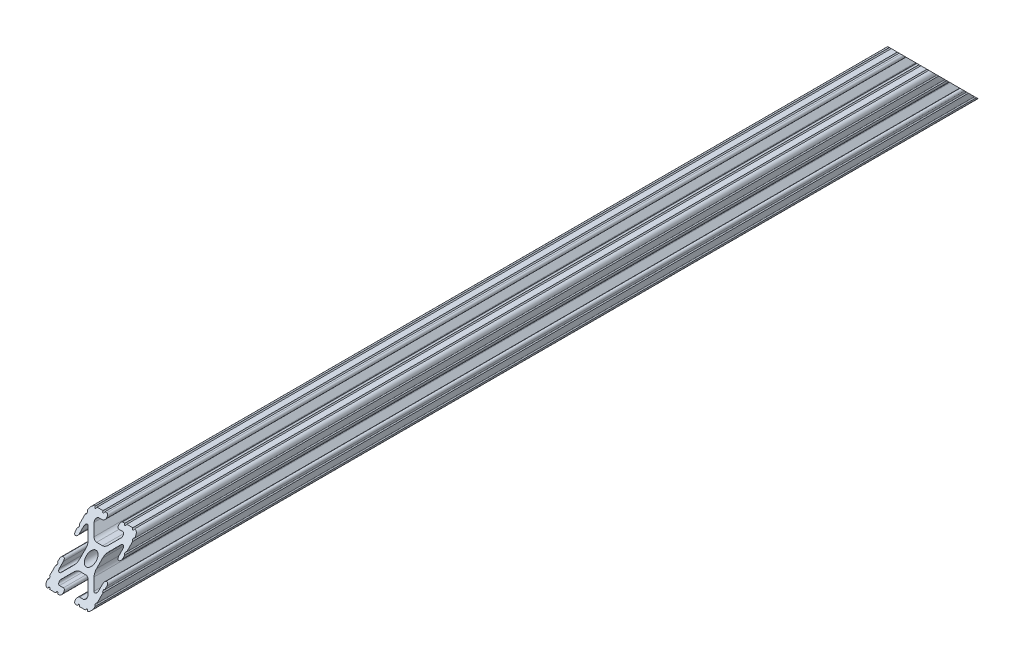
SolidWorks part; units mm, degrees
ref_plane "Front Plane" through (0, 0, 0) normal (0, 0, 1) x (1, 0, 0)
ref_plane "Top Plane" through (0, 0, 0) normal (0, 1, 0) x (1, 0, 0)
ref_plane "Right Plane" through (0, 0, 0) normal (1, 0, 0) x (0, 0, -1)
sketch "Sketch1" plane through (0, 0, 0) normal (0, 0, 1) x (1, 0, 0)
  line L0 (-12.7, -6.3331) -> (-12.7, -9.5504)
  line L1 (-9.5504, -12.7) -> (-6.3331, -12.7)
  line L2 (-5.3171, -12.7) -> (-4.3434, -12.7)
  line L3 (-4.3434, -10.4902) -> (-6.4748, -10.4902)
  line L4 (-7.1932, -8.7558) -> (-3.8632, -5.4257)
  line L5 (-1.6181, -4.4958) -> (1.6181, -4.4958)
  line L6 (3.8632, -5.4257) -> (7.1932, -8.7558)
  line L7 (6.4748, -10.4902) -> (4.3434, -10.4902)
  line L8 (4.3434, -12.7) -> (5.3171, -12.7)
  line L9 (6.3331, -12.7) -> (9.5504, -12.7)
  line L10 (12.7, -9.5504) -> (12.7, -6.3331)
  line L11 (12.7, -5.3171) -> (12.7, -4.3434)
  line L12 (10.4902, -4.3434) -> (10.4902, -6.4748)
  line L13 (8.7558, -7.1932) -> (5.4257, -3.8632)
  line L14 (4.4958, -1.6181) -> (4.4958, 1.6181)
  line L15 (5.4257, 3.8632) -> (8.7558, 7.1932)
  line L16 (10.4902, 6.4748) -> (10.4902, 4.3434)
  line L17 (12.7, 4.3434) -> (12.7, 5.3171)
  line L18 (12.7, 6.3331) -> (12.7, 9.5504)
  line L19 (9.5504, 12.7) -> (6.3331, 12.7)
  line L20 (5.3171, 12.7) -> (4.3434, 12.7)
  line L21 (4.3434, 10.4902) -> (6.4748, 10.4902)
  line L22 (7.1932, 8.7558) -> (3.8632, 5.4257)
  line L23 (1.6181, 4.4958) -> (-1.6181, 4.4958)
  line L24 (-3.8632, 5.4257) -> (-7.1932, 8.7558)
  line L25 (-6.4748, 10.4902) -> (-4.3434, 10.4902)
  line L26 (-4.3434, 12.7) -> (-5.3171, 12.7)
  line L27 (-6.3331, 12.7) -> (-9.5504, 12.7)
  line L28 (-12.7, 9.5504) -> (-12.7, 6.3331)
  line L29 (-12.7, 5.3171) -> (-12.7, 4.3434)
  line L30 (-10.4902, 4.3434) -> (-10.4902, 6.4748)
  line L31 (-8.7558, 7.1932) -> (-5.4257, 3.8632)
  line L32 (-4.4958, 1.6181) -> (-4.4958, -1.6181)
  line L33 (-5.4257, -3.8632) -> (-8.7558, -7.1932)
  line L34 (-10.4902, -6.4748) -> (-10.4902, -4.3434)
  line L35 (-12.7, -4.3434) -> (-12.7, -5.3171)
  circle A0 centre (0, 0) radius 2.6035
  arc A1 (-12.7, -5.3171) -> (-12.7, -6.3331) centre (-12.7, -5.8251) cw
  arc A2 (-12.7, -9.5504) -> (-12.6998, -10.5664) centre (-12.7, -10.0584) cw
  arc A3 (-12.6998, -10.5664) -> (-10.5664, -12.6998) centre (-10.5918, -10.5918) ccw
  arc A4 (-10.5664, -12.6998) -> (-9.5504, -12.7) centre (-10.0584, -12.7) cw
  arc A5 (-6.3331, -12.7) -> (-5.3171, -12.7) centre (-5.8251, -12.7) cw
  arc A6 (-4.3434, -12.7) -> (-4.3434, -10.4902) centre (-4.3434, -11.5951) ccw
  arc A7 (-6.4748, -10.4902) -> (-7.1932, -8.7558) centre (-6.4748, -9.4742) cw
  arc A8 (-3.8632, -5.4257) -> (-1.6181, -4.4958) centre (-1.6181, -7.6708) cw
  arc A9 (1.6181, -4.4958) -> (3.8632, -5.4257) centre (1.6181, -7.6708) cw
  arc A10 (7.1932, -8.7558) -> (6.4748, -10.4902) centre (6.4748, -9.4742) cw
  arc A11 (4.3434, -10.4902) -> (4.3434, -12.7) centre (4.3434, -11.5951) ccw
  arc A12 (5.3171, -12.7) -> (6.3331, -12.7) centre (5.8251, -12.7) cw
  arc A13 (9.5504, -12.7) -> (10.5664, -12.6998) centre (10.0584, -12.7) cw
  arc A14 (10.5664, -12.6998) -> (12.6998, -10.5664) centre (10.5918, -10.5918) ccw
  arc A15 (12.6998, -10.5664) -> (12.7, -9.5504) centre (12.7, -10.0584) cw
  arc A16 (12.7, -6.3331) -> (12.7, -5.3171) centre (12.7, -5.8251) cw
  arc A17 (12.7, -4.3434) -> (10.4902, -4.3434) centre (11.5951, -4.3434) ccw
  arc A18 (10.4902, -6.4748) -> (8.7558, -7.1932) centre (9.4742, -6.4748) cw
  arc A19 (5.4257, -3.8632) -> (4.4958, -1.6181) centre (7.6708, -1.6181) cw
  arc A20 (4.4958, 1.6181) -> (5.4257, 3.8632) centre (7.6708, 1.6181) cw
  arc A21 (8.7558, 7.1932) -> (10.4902, 6.4748) centre (9.4742, 6.4748) cw
  arc A22 (10.4902, 4.3434) -> (12.7, 4.3434) centre (11.5951, 4.3434) ccw
  arc A23 (12.7, 5.3171) -> (12.7, 6.3331) centre (12.7, 5.8251) cw
  arc A24 (12.7, 9.5504) -> (12.6998, 10.5664) centre (12.7, 10.0584) cw
  arc A25 (12.6998, 10.5664) -> (10.5664, 12.6998) centre (10.5918, 10.5918) ccw
  arc A26 (10.5664, 12.6998) -> (9.5504, 12.7) centre (10.0584, 12.7) cw
  arc A27 (6.3331, 12.7) -> (5.3171, 12.7) centre (5.8251, 12.7) cw
  arc A28 (4.3434, 12.7) -> (4.3434, 10.4902) centre (4.3434, 11.5951) ccw
  arc A29 (6.4748, 10.4902) -> (7.1932, 8.7558) centre (6.4748, 9.4742) cw
  arc A30 (3.8632, 5.4257) -> (1.6181, 4.4958) centre (1.6181, 7.6708) cw
  arc A31 (-1.6181, 4.4958) -> (-3.8632, 5.4257) centre (-1.6181, 7.6708) cw
  arc A32 (-7.1932, 8.7558) -> (-6.4748, 10.4902) centre (-6.4748, 9.4742) cw
  arc A33 (-4.3434, 10.4902) -> (-4.3434, 12.7) centre (-4.3434, 11.5951) ccw
  arc A34 (-5.3171, 12.7) -> (-6.3331, 12.7) centre (-5.8251, 12.7) cw
  arc A35 (-9.5504, 12.7) -> (-10.5664, 12.6998) centre (-10.0584, 12.7) cw
  arc A36 (-10.5664, 12.6998) -> (-12.6998, 10.5664) centre (-10.5918, 10.5918) ccw
  arc A37 (-12.6998, 10.5664) -> (-12.7, 9.5504) centre (-12.7, 10.0584) cw
  arc A38 (-12.7, 6.3331) -> (-12.7, 5.3171) centre (-12.7, 5.8251) cw
  arc A39 (-12.7, 4.3434) -> (-10.4902, 4.3434) centre (-11.5951, 4.3434) ccw
  arc A40 (-10.4902, 6.4748) -> (-8.7558, 7.1932) centre (-9.4742, 6.4748) cw
  arc A41 (-5.4257, 3.8632) -> (-4.4958, 1.6181) centre (-7.6708, 1.6181) cw
  arc A42 (-4.4958, -1.6181) -> (-5.4257, -3.8632) centre (-7.6708, -1.6181) cw
  arc A43 (-8.7558, -7.1932) -> (-10.4902, -6.4748) centre (-9.4742, -6.4748) cw
  arc A44 (-10.4902, -4.3434) -> (-12.7, -4.3434) centre (-11.5951, -4.3434) ccw
extrude "Boss-Extrude1" add sketch "Sketch1" against normal blind 475.8258
ref_plane "Plane1" through (0, -6.35, -6.35) normal (0, 0.7071, 0.7071) x (1, 0, 0)
sketch "Sketch2" plane through (0, -6.35, -6.35) normal (0, 0.7071, 0.7071) x (1, 0, 0)
  line L1 (-26.2789, 89.8191) -> (37.8258, 89.8191)
  line L2 (-26.2789, 89.8191) -> (-26.2789, -16.6052)
  line L3 (-26.2789, -16.6052) -> (37.8258, -16.6052)
  line L4 (37.8258, 89.8191) -> (37.8258, -16.6052)
extrude "Cut-Extrude1" cut sketch "Sketch2" along normal blind 27.94
ref_plane "Plane2" through (0, 231.5629, -231.5629) normal (0, 0.7071, -0.7071) x (-1, 0, 0)
sketch "Sketch3" plane through (0, 231.5629, -231.5629) normal (0, 0.7071, -0.7071) x (-1, 0, 0)
  line L1 (89.1892, -269.4453) -> (-42.2056, -269.4453)
  line L2 (89.1892, -269.4453) -> (89.1892, -416.4122)
  line L3 (89.1892, -416.4122) -> (-42.2056, -416.4122)
  line L4 (-42.2056, -269.4453) -> (-42.2056, -416.4122)
extrude "Cut-Extrude2" cut sketch "Sketch3" along normal blind 24.638
